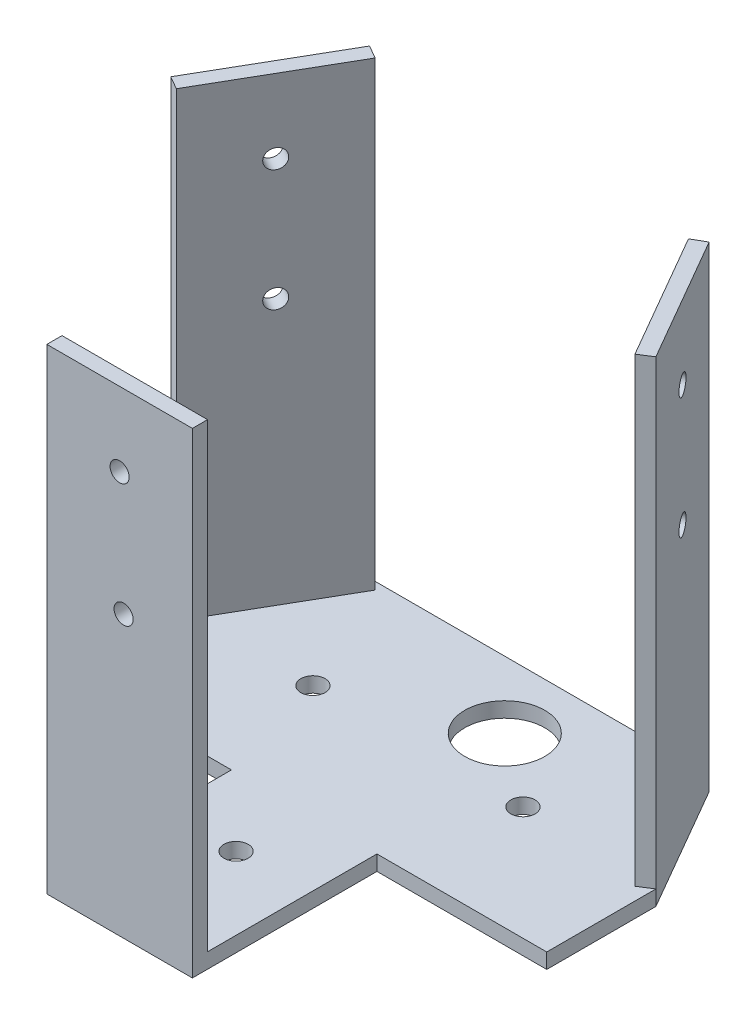
SolidWorks part; units mm, degrees
ref_plane "Front Plane" through (0, 0, 0) normal (0, 0, 1) x (1, 0, 0)
ref_plane "Top Plane" through (0, 0, 0) normal (0, 1, 0) x (1, 0, 0)
ref_plane "Right Plane" through (0, 0, 0) normal (1, 0, 0) x (0, 0, -1)
sketch "Sketch1" plane through (0, 0, 0) normal (0, 1, 0) x (1, 0, 0)
  line L0 (0, 11.43) -> (7.62, 24.6282)
  line L1 (0, 0) -> (50.8, 0)
  line L2 (0, 0) -> (0, 11.43)
  line L3 (0, 11.43) -> (50.8, 11.43)
  line L4 (50.8, 0) -> (50.8, 11.43)
  line L5 (50.8, 11.43) -> (43.18, 24.6282)
  line L6 (7.62, 24.6282) -> (43.18, 24.6282)
  line L7 (3.81, 18.0291) -> (44.3832, -5.3958) construction
  line L8 (17.78, 0) -> (33.02, 0)
  line L9 (17.78, 0) -> (17.78, -19.3279)
  line L10 (17.78, -19.3279) -> (33.02, -19.3279)
  line L11 (33.02, 0) -> (33.02, -19.3279)
  line L12 (46.99, 18.0291) -> (8.5613, -4.1577) construction
  line L13 (25.4, -19.3279) -> (25.4, 20.0669) construction
  circle A2 centre (36.3985, 11.9141) radius 1.27
  circle A5 centre (14.4015, 11.9141) radius 1.27
  circle A8 centre (25.4, -7.1359) radius 1.27
  point P23 (25.4, 5.5641)
  dimension "D13" = 2.54
  dimension "D16" = 12.7
  dimension "D21" = 2.54
  dimension "D24" = 12.7
  dimension "D26" = 2.54
  dimension "D1" = 50.8
  dimension "D2" = 11.43
  dimension "D3" = 30
  dimension "D4" = 15.24
  dimension "D5" = 30
  dimension "D6" = 15.24
  dimension "D7" = 15.24
  dimension "D8" = 24.892
  dimension "D9" = 17.78
  dimension "D10" = 12.7
extrude "Boss-Extrude2" add sketch "Sketch1" along normal blind 1.5875
sketch "Sketch2" plane through (0, 1.5875, 0) normal (0, 1, 0) x (1, 0, 0)
  line L0 (17.78, 0) -> (17.78, -19.3279) construction
  line L1 (33.02, -19.3279) -> (17.78, -19.3279)
  line L2 (33.02, -19.3279) -> (33.02, -17.7404)
  line L3 (33.02, -17.7404) -> (17.78, -17.7404)
  line L4 (17.78, -19.3279) -> (17.78, -17.7404)
  line L5 (0, 11.43) -> (7.62, 24.6282)
  line L6 (7.62, 24.6282) -> (8.9948, 23.8345)
  line L7 (8.9948, 23.8345) -> (1.3748, 10.6362)
  line L8 (1.3748, 10.6362) -> (0, 11.43)
  line L9 (50.8, 11.43) -> (43.18, 24.6282)
  line L10 (50.8, 11.43) -> (43.18, 24.6282) construction
  line L11 (43.18, 24.6282) -> (41.8064, 23.8352)
  line L12 (41.8064, 23.8352) -> (49.46, 10.5787)
  line L13 (49.46, 10.5787) -> (50.8, 11.43)
  dimension "D1" = 1.5875
  dimension "D2" = 1.5875
  dimension "D3" = 1.5875
extrude "Boss-Extrude3" add sketch "Sketch2" along normal blind 48.26
sketch "Sketch3" plane through (0, 1.5875, 0) normal (0, 1, 0) x (1, 0, 0)
  line L0 (7.62, 24.6282) -> (43.18, 24.6282) construction
  circle A0 centre (28.7785, 17.628) radius 4.191
  circle A1 centre (36.3985, 11.9141) radius 1.27 construction
  dimension "D1" = 8.382
  dimension "D2" = 7.0002
  dimension "D3" = 7.62
extrude "Cut-Extrude1" cut sketch "Sketch3" against normal blind 2.54
sketch "Sketch4" plane through (43.0493, 0, -24.8545) normal (0.866, 0, -0.5) x (-0.5, 0, -0.866)
  line L0 (-0.2613, 49.8475) -> (-0.2613, 1.5875) construction
  line L1 (-15.5013, 49.8475) -> (-0.2613, 49.8475) construction
  circle A0 centre (-7.8813, 42.1025) radius 1
  circle A1 centre (-7.8813, 29.4025) radius 1
  dimension "D1" = 7.62
  dimension "D2" = 7.62
  dimension "D3" = 7.745
  dimension "D4" = 12.7
  dimension "D5" = 2
  dimension "D6" = 2
extrude "Cut-Extrude2" cut sketch "Sketch4" against normal blind 2.54
sketch "Sketch5" plane through (-4.9493, 0, -2.8575) normal (-0.866, 0, -0.5) x (-0.5, 0, 0.866)
  line L0 (-9.8987, 49.8475) -> (-9.8987, 1.5875) construction
  line L1 (-25.1387, 49.8475) -> (-9.8987, 49.8475) construction
  circle A0 centre (-17.5187, 42.1025) radius 1
  circle A1 centre (-17.5187, 29.4025) radius 1
  dimension "D1" = 7.62
  dimension "D2" = 7.62
  dimension "D3" = 2
  dimension "D4" = 2
  dimension "D5" = 7.745
  dimension "D6" = 12.7
extrude "Cut-Extrude3" cut sketch "Sketch5" against normal blind 2.54
sketch "Sketch6" plane through (0, 0, 19.3279) normal (0, 0, 1) x (1, 0, 0)
  line L0 (17.78, 49.8475) -> (33.02, 49.8475) construction
  line L1 (17.78, 49.8475) -> (17.78, 0) construction
  circle A0 centre (25.4, 42.1025) radius 1
  circle A1 centre (25.8182, 29.4025) radius 1
  dimension "D1" = 2
  dimension "D2" = 2
  dimension "D3" = 7.745
  dimension "D4" = 12.7
  dimension "D5" = 7.62
extrude "Cut-Extrude4" cut sketch "Sketch6" against normal blind 2.54
